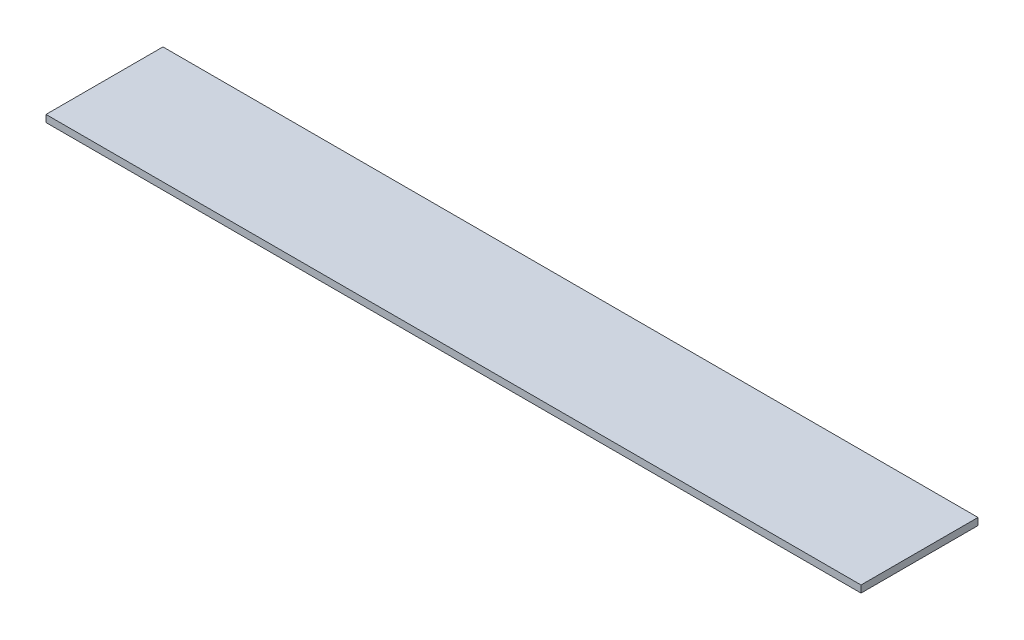
SolidWorks part; units mm, degrees
ref_plane "Front Plane" through (0, 0, 0) normal (0, 0, 1) x (1, 0, 0)
ref_plane "Top Plane" through (0, 0, 0) normal (0, 1, 0) x (1, 0, 0)
ref_plane "Right Plane" through (0, 0, 0) normal (1, 0, 0) x (0, 0, -1)
sketch "Sketch1" plane through (0, 0, 0) normal (0, 1, 0) x (1, 0, 0)
  line L1 (685.8, 98.425) -> (-685.8, 98.425)
  line L2 (685.8, 98.425) -> (685.8, -98.425)
  line L3 (685.8, -98.425) -> (-685.8, -98.425)
  line L4 (-685.8, 98.425) -> (-685.8, -98.425)
  line L5 (0, -98.425) -> (0, 98.425) construction
  line L6 (685.8, 0) -> (-685.8, 0) construction
  point P0 (0, 0)
  dimension "D1" = 1371.6
  dimension "D2" = 196.85
extrude "Boss-Extrude1" add sketch "Sketch1" along normal blind 11.8872
